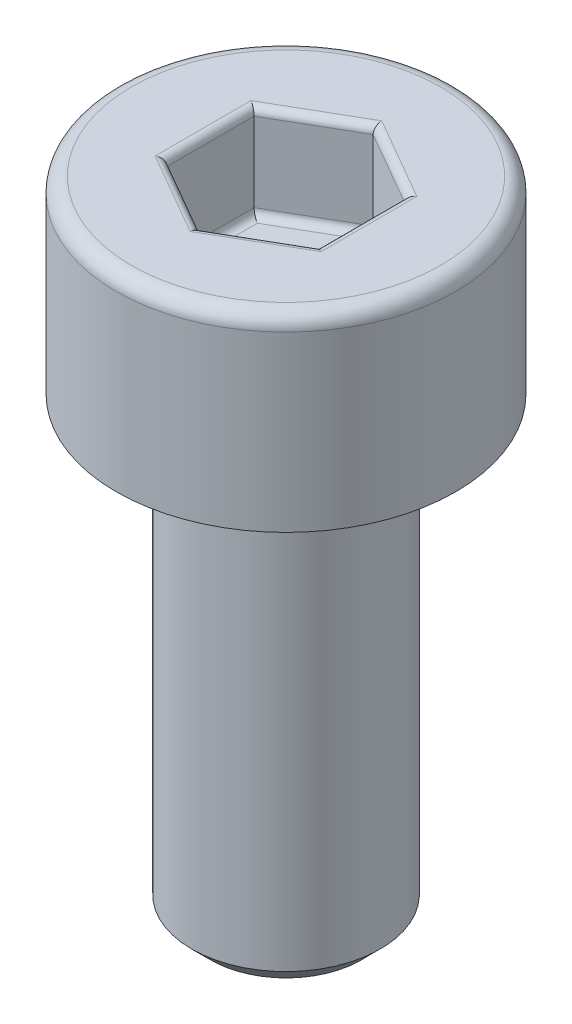
SolidWorks part; units mm, degrees
ref_plane "Front Plane" through (0, 0, 0) normal (0, 0, 1) x (1, 0, 0)
ref_plane "Top Plane" through (0, 0, 0) normal (0, 1, 0) x (1, 0, 0)
ref_plane "Right Plane" through (0, 0, 0) normal (1, 0, 0) x (0, 0, -1)
sketch "Sketch1" plane through (0, 0, 0) normal (0, 0, 1) x (1, 0, 0)
  line L0 (0, 0) -> (0, -47.0967) construction
  line L1 (0, -8.5) -> (-1.25, -8.5)
  line L2 (-1.25, -8.5) -> (-1.25, -2.5)
  line L3 (-1.25, -2.5) -> (-2.25, -2.5)
  line L4 (-2.25, -2.5) -> (-2.25, 0)
  line L5 (-2.25, 0) -> (0, 0)
  line L6 (0, 0) -> (0, -8.5)
  dimension "d" = 2.5
  dimension "l" = 8.5
  dimension "k" = 2.5
  dimension "dk" = 4.5
revolve "Revolve1" add sketch "Sketch1" angle 360 about L0
chamfer "Chamfer1" distance 0.25 angle 45 2 edges at (0, -2.5, 1.25) (0, -8.5, 1.25)
fillet "Fillet1" radius 0.2 1 edges at (0, 0, 2.25)
sketch "Sketch2" plane through (0, 0, 0) normal (0, 1, 0) x (1, 0, 0)
  line L1 (0, 1.1547) -> (-1, 0.5774)
  line L2 (-1, 0.5774) -> (-1, -0.5774)
  line L3 (-1, -0.5774) -> (0, -1.1547)
  line L4 (0, -1.1547) -> (1, -0.5774)
  line L5 (1, -0.5774) -> (1, 0.5774)
  line L6 (1, 0.5774) -> (0, 1.1547)
  circle A0 centre (0, 0) radius 1 construction
  dimension "s" = 2
extrude "Cut-Extrude1" cut sketch "Sketch2" against normal blind 1.25
fillet "Fillet2" radius 0.1 12 edges at (-0.5, 0, -0.866) (-1, 0, 0) (-0.5, 0, 0.866) (0.5, 0, 0.866) (1, 0, 0) (0.5, 0, -0.866) (1, -1.25, 0) (0.5, -1.25, 0.866) (-0.5, -1.25, 0.866) (-1, -1.25, 0) (-0.5, -1.25, -0.866) (0.5, -1.25, -0.866)
